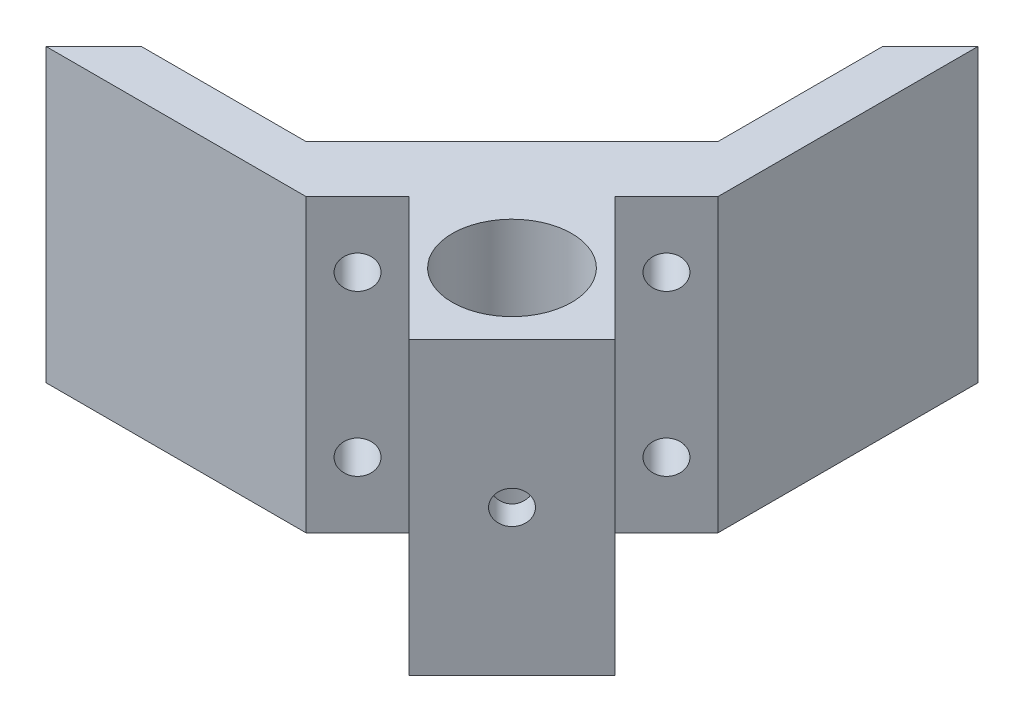
SolidWorks part; units mm, degrees
material "PET"
ref_plane "Front Plane" through (0, 0, 0) normal (0, 0, 1) x (1, 0, 0)
ref_plane "Top Plane" through (0, 0, 0) normal (0, 1, 0) x (1, 0, 0)
ref_plane "Right Plane" through (0, 0, 0) normal (1, 0, 0) x (0, 0, -1)
sketch "Sketch2" plane through (0, 0, 0) normal (0, 1, 0) x (1, 0, 0)
  line L0 (-40, -40) -> (40, 40)
  line L3 (-40, -40) -> (40, -40)
  line L4 (40, 40) -> (40, -40)
  line L5 (-17.6777, -17.6777) -> (17.6777, 17.6777)
  line L6 (-40, -40) -> (40, 40) construction
  line L7 (-17.6777, -17.6777) -> (-3.5355, -31.8198)
  line L8 (17.6777, 17.6777) -> (31.8198, 3.5355)
  line L9 (-3.5355, -31.8198) -> (31.8198, 3.5355)
  line L10 (4.6447, -40) -> (40, -4.6447)
  line L11 (31.8198, 3.5355) -> (31.8198, 31.8198)
  line L12 (-3.5355, -31.8198) -> (-31.8198, -31.8198)
  point P0 (0, 0)
  dimension "D1" = 50
  dimension "D2" = 25
  dimension "D3" = 20
  dimension "D4" = 80
  dimension "D5" = 40
extrude "Boss-Extrude1" add sketch "Sketch2" along normal blind 50 contours L4 L3 L0
sketch "Sketch4" plane through (0, 50, 0) normal (0, 1, 0) x (1, 0, 0)
  line L0 (-40, -40) -> (40, 40)
  line L1 (-40, -40) -> (40, -40)
  line L2 (40, 40) -> (40, -40)
  line L3 (-17.6777, -17.6777) -> (17.6777, 17.6777)
  line L4 (-40, -40) -> (40, 40) construction
  line L5 (-17.6777, -17.6777) -> (-3.5355, -31.8198)
  line L6 (17.6777, 17.6777) -> (31.8198, 3.5355)
  line L7 (-3.5355, -31.8198) -> (31.8198, 3.5355)
  line L8 (4.6447, -40) -> (40, -4.6447)
  line L9 (31.8198, 3.5355) -> (31.8198, 31.8198)
  line L10 (-3.5355, -31.8198) -> (-31.8198, -31.8198)
  point P0 (0, 0)
  line M5 (40, 40) -> (-40, -40)
  line M7 (40, -40) -> (40, 40)
  dimension "D1" = 50
  dimension "D2" = 25
  dimension "D3" = 80
  dimension "D4" = 40
  dimension "D5" = 20
extrude "Cut-Extrude1" cut sketch "Sketch4" against normal through all contours L5 L7 L6 L0 | L6 L9 L0 | L10 L5 M5 | L8 L1 M7
sketch "Sketch5" plane through (22.3223, 0, 22.3223) normal (0.7071, 0, 0.7071) x (0.7071, 0, -0.7071)
  line L0 (-25, 50) -> (25, 50) construction
  line L1 (-12.5, 50) -> (12.5, 50)
  line L2 (-12.5, 50) -> (-12.5, 0)
  line L3 (-12.5, 0) -> (12.5, 0)
  line L4 (12.5, 50) -> (12.5, 0)
  line L5 (-12.5, 50) -> (12.5, 0) construction
  line L6 (-12.5, 0) -> (12.5, 50) construction
  line L7 (-25, 0) -> (-25, 50) construction
  point P0 (0, 25)
  dimension "D1" = 25
  dimension "D2" = 25
  dimension "D3" = 25
  dimension "D4" = 50
extrude "Boss-Extrude2" add sketch "Sketch5" along normal blind 30
hole_wizard "Ø20.5 (20.5) Diameter Hole1" positions "Sketch6" profile "Sketch8" hole size "Ø20.5" standard "ISO" end condition through all
sketch "Sketch6" plane through (0, 50, 0) normal (0, 1, 0) x (1, 0, 0)
  line L0 (31.1612, -13.4835) -> (34.6967, -52.3744)
  line L2 (13.4835, -31.1612) -> (52.3744, -34.6967)
  point P12 (32.9289, -32.9289)
  point P17 (0, 0)
  point P20 (0, 0)
  point P21 (0, 0)
  point P25 (0, 0)
  point P26 (0, 0)
  point P28 (0, 0)
  point P30 (0, 0)
  point P31 (32.9289, -32.9289)
sketch "Sketch8" plane through (32.9289, 50, 32.9289) normal (1, 0, 0) x (0, 0, 1)
  line L0 (0, 0) -> (0, 50)
  line L1 (0, 50) -> (10.25, 50)
  line L2 (10.25, 50) -> (10.25, 0)
  line L5 (10.25, 0) -> (0, 0)
  line L11 (0, -6.35) -> (0, 107.95) construction
  dimension "Thru Hole Dia." = 20.5
  dimension "Thru Hole Depth" = 50
hole_wizard "Ø5.7 (5.7) Diameter Hole1" positions "Sketch10" profile "Sketch11" hole size "Ø5.7" standard "ISO"
sketch "Sketch10" plane through (43.5355, 0, 43.5355) normal (0.7071, 0, 0.7071) x (0.7071, 0, -0.7071)
  line L0 (-12.5, 50) -> (12.5, 0)
  line L2 (12.5, 50) -> (-12.5, 0)
  point P13 (0, 25)
sketch "Sketch11" plane through (43.5355, 25, 43.5355) normal (0, 1, 0) x (0.7071, 0, -0.7071)
  line L0 (0, 0) -> (0, 4.75)
  line L1 (0, 4.75) -> (2.85, 4.75)
  line L2 (2.85, 4.75) -> (2.85, 0)
  line L5 (2.85, 0) -> (0, 0)
  line L11 (0, -6.35) -> (0, 107.95) construction
  dimension "Thru Hole Dia." = 5.7
  dimension "Thru Hole Depth" = 4.75
hole_wizard "Ø5.7 (5.7) Diameter Hole2" positions "Sketch17" profile "Sketch18" hole size "Ø5.7" standard "ISO"
sketch "Sketch17" plane through (22.3223, 0, 22.3223) normal (0.7071, 0, 0.7071) x (0.7071, 0, -0.7071)
  line L0 (-25, 50) -> (-12.5, 50) construction
  line L1 (-25, 0) -> (-25, 50) construction
  point P0 (-18.75, 38.75)
  point P28 (18.75, 38.75)
  point P29 (18.75, 11.25)
  point P30 (-18.75, 11.25)
  dimension "D1" = 11.25
  dimension "D2" = 6.25
  dimension "D3" = 2
  dimension "D4" = 2
sketch "Sketch18" plane through (9.0641, 38.75, 35.5806) normal (0, 1, 0) x (0.7071, 0, -0.7071)
  line L0 (0, 0) -> (0, 13.281)
  line L1 (0, 13.281) -> (2.85, 11.5685)
  line L2 (2.85, 11.5685) -> (2.85, 0)
  line L5 (2.85, 0) -> (0, 0)
  line L10 (0, 13.281) -> (-2.85, 11.5685) construction
  line L11 (0, -6.35) -> (0, 107.95) construction
  dimension "Hole Dia." = 5.7
  dimension "Hole Depth" = 11.5685
  dimension "Drill Angle" = 118
